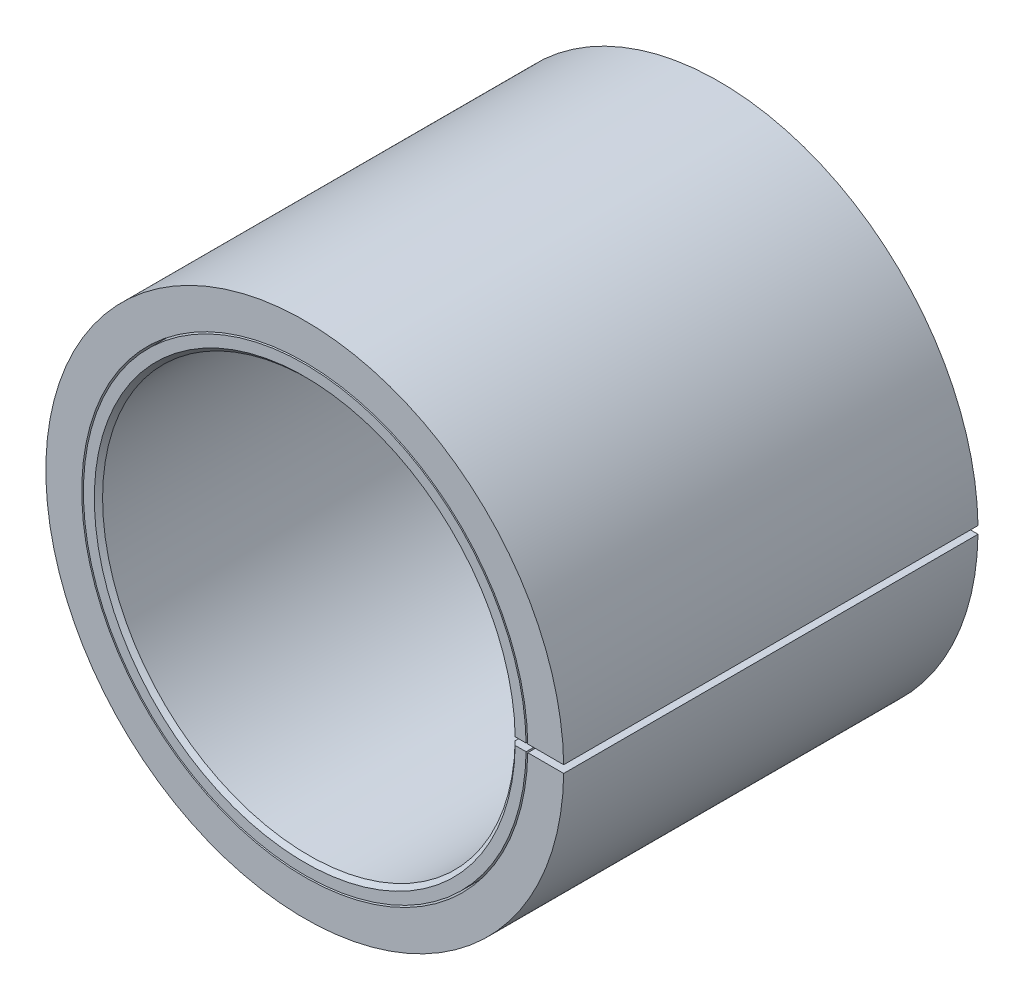
SolidWorks part; units mm, degrees
ref_plane "Front Plane" through (0, 0, 0) normal (0, 0, 1) x (1, 0, 0)
ref_plane "Top Plane" through (0, 0, 0) normal (0, 1, 0) x (1, 0, 0)
ref_plane "Right Plane" through (0, 0, 0) normal (1, 0, 0) x (0, 0, -1)
sketch "Sketch1" plane through (0, 0, 0) normal (0, 0, 1) x (1, 0, 0)
  circle A0 centre (0, 0) radius 3.9687
  circle A1 centre (0, 0) radius 3.1623
  point P4 (0, 3.9687)
  dimension "ID" = 6.3246
  dimension "OD" = 7.9375
sketch "Sketch2" plane through (0, 0, 0) normal (1, 0, 0) x (0, 0, -1)
  line L0 (3.175, 0) -> (-3.175, 0) construction
  line L1 (3.175, 3.9687) -> (-3.175, 3.9687) construction
  point P4 (0, 0)
  point P9 (0, 3.9687)
  dimension "Length" = 6.35
sketch "Sketch3" plane through (0, 0, 0) normal (0, 0, 1) x (1, 0, 0)
  circle A0 centre (0, 0) radius 3.9687 construction
  circle A1 centre (0, 0) radius 3.1623 construction
  circle A2 centre (0, 0) radius 3.9687
  circle A3 centre (0, 0) radius 3.1623
extrude "Boss-Extrude1" add sketch "Sketch3" against normal up to vertex (3.175 mm away) and the other way up to vertex (3.175 mm away) up to point (0, 0, -3.175) other way up to point (0, 0, 3.175)
sketch "Sketch4" plane through (0, 0, 3.175) normal (0, 0, 1) x (1, 0, 0)
  circle A0 centre (0, 0) radius 3.3927
  circle A1 centre (0, 0) radius 3.1623 construction
  point P3 (0, 3.1623)
  point P4 (0, 3.3927)
  dimension "D1" = 0.2304
extrude "Cut-Extrude-Thin1" cut sketch "Sketch4" against normal through all thin
chamfer "Chamfer1" distance 0.0632 angle 45 2 edges at (3.1623, 0, 3.175) (3.1623, 0, -3.175)
sketch "Sketch5" plane through (0, 0, 3.175) normal (0, 0, 1) x (1, 0, 0)
  line L0 (0, 0) -> (4.0538, 0)
  circle A6 centre (0, 0) radius 3.9687 construction
  dimension "D1" = 0.0851
extrude "Cut-Extrude-Thin3" cut sketch "Sketch5" against normal through all and the other way through all thin thin type mid plane wall 0.1152
equation "\"D1@Sketch4\"=(\"OD@Sketch1\"-\"ID@Sketch1\")/7"
equation "\"D1@Chamfer1\"=\"ID@Sketch1\"*.01"
equation "\"D5@Cut-Extrude-Thin3\"=\"D1@Sketch4\"*.5"
